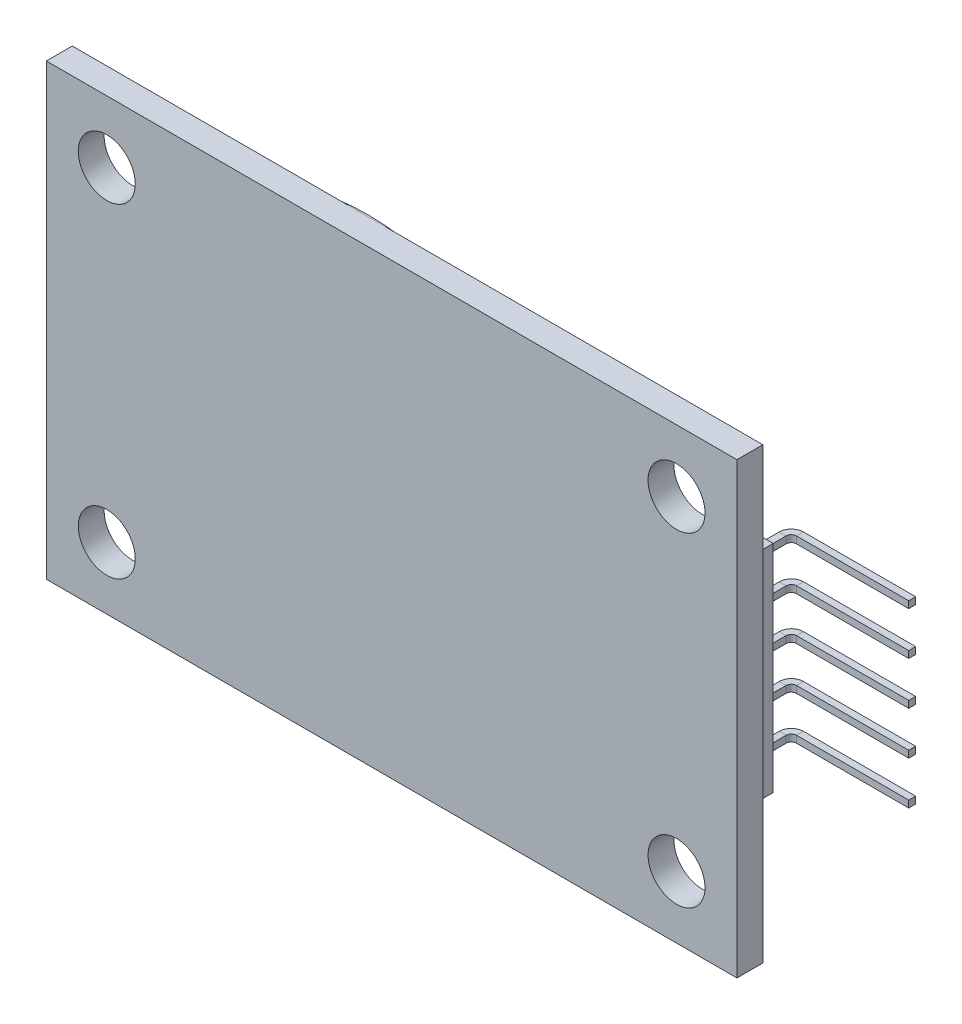
SolidWorks part; units mm, degrees
ref_plane "前视基准面" through (0, 0, 0) normal (0, 0, 1) x (1, 0, 0)
ref_plane "上视基准面" through (0, 0, 0) normal (0, 1, 0) x (1, 0, 0)
ref_plane "右视基准面" through (0, 0, 0) normal (1, 0, 0) x (0, 0, -1)
sketch "草图1" plane through (0, 0, 0) normal (0, 0, 1) x (1, 0, 0)
  line L1 (-20, 13) -> (20, 13)
  line L2 (-20, 13) -> (-20, -13)
  line L3 (-20, -13) -> (20, -13)
  line L4 (20, 13) -> (20, -13)
  line L5 (-20, 13) -> (20, -13) construction
  line L6 (-20, -13) -> (20, 13) construction
  point P0 (0, 0)
  dimension "D1" = 40
  dimension "D2" = 26
extrude "凸台-拉伸1" add sketch "草图1" along normal blind 1.5
sketch "草图2" plane through (0, 0, 1.5) normal (0, 0, 1) x (1, 0, 0)
  line L1 (-16.5, 9.4) -> (16.5, 9.4)
  line L2 (-16.5, 9.4) -> (-16.5, -9.4)
  line L3 (-16.5, -9.4) -> (16.5, -9.4)
  line L4 (16.5, 9.4) -> (16.5, -9.4)
  line L5 (-16.5, 9.4) -> (16.5, -9.4) construction
  line L6 (-16.5, -9.4) -> (16.5, 9.4) construction
  circle A0 centre (-16.5, 9.4) radius 1.65
  circle A1 centre (16.5, 9.4) radius 1.65
  circle A2 centre (16.5, -9.4) radius 1.65
  circle A3 centre (-16.5, -9.4) radius 1.65
  point P0 (0, 0)
  dimension "D3" = 3.3
  dimension "D4" = 3.3
  dimension "D5" = 3.3
  dimension "D6" = 3.3
  dimension "D1" = 33
  dimension "D2" = 18.8
extrude "切除-拉伸1" cut sketch "草图2" against normal blind 1.5 contours A0 | A1 | A3 | A2
sketch "草图3" plane through (0, 0, 0) normal (0, 0, -1) x (-1, 0, 0)
  line L0 (0, 0) -> (20, 0) construction
  line L1 (20, 13) -> (20, -13) construction
  circle A0 centre (3, 0) radius 13
  dimension "D1" = 17
extrude "凸台-拉伸2" add sketch "草图3" along normal blind 0.1 contours A0
sketch "草图4" plane through (0, 0, 0) normal (0, 0, -1) x (-1, 0, 0)
  line L0 (-20, 0) -> (20, 0) construction
  line L1 (-20, -13) -> (-20, 13) construction
  line L2 (20, 13) -> (20, -13) construction
  line L4 (-18.5, 6.25) -> (-16, 6.25)
  line L5 (-18.5, 6.25) -> (-18.5, -6.25)
  line L6 (-18.5, -6.25) -> (-16, -6.25)
  line L7 (-16, 6.25) -> (-16, -6.25)
  line L8 (-18.5, 6.25) -> (-16, -6.25) construction
  line L9 (-18.5, -6.25) -> (-16, 6.25) construction
  point P6 (-17.25, 0)
  dimension "D1" = 2.5
  dimension "D2" = 12.5
  dimension "D3" = 1.5
extrude "凸台-拉伸3" add sketch "草图4" along normal blind 2.1
sketch "草图5" plane through (0, 0, -2.1) normal (0, 0, -1) x (-1, 0, 0)
  line L0 (-18.5, 6.25) -> (-18.5, 3.75) construction
  line L1 (-18.5, 6.25) -> (-18.5, -6.25) construction
  line L2 (-18.5, 3.75) -> (-16, 3.75) construction
  line L3 (-16, -6.25) -> (-16, 6.25) construction
  line L4 (-18.5, 5) -> (-16, 5) construction
  line L5 (-16, 5) -> (-17.25, 3.75) construction
  line L6 (-17.25, 3.75) -> (-17.25, 5) construction
  line L7 (-17.45, 2.7) -> (-17.05, 2.7)
  line L8 (-17.45, 5.2) -> (-17.05, 5.2)
  line L9 (-17.45, 5.2) -> (-17.45, 4.8)
  line L10 (-17.45, 4.8) -> (-17.05, 4.8)
  line L11 (-17.05, 5.2) -> (-17.05, 4.8)
  line L12 (-17.45, 5.2) -> (-17.05, 4.8) construction
  line L13 (-17.45, 4.8) -> (-17.05, 5.2) construction
  line L14 (-17.45, 2.7) -> (-17.45, 2.3)
  line L15 (-17.45, 2.3) -> (-17.05, 2.3)
  line L16 (-17.05, 2.7) -> (-17.05, 2.3)
  line L17 (-17.45, 2.7) -> (-17.05, 2.3) construction
  line L18 (-17.45, 2.3) -> (-17.05, 2.7) construction
  line L19 (-17.45, 0.2) -> (-17.05, 0.2)
  line L20 (-17.45, 0.2) -> (-17.45, -0.2)
  line L21 (-17.45, -0.2) -> (-17.05, -0.2)
  line L22 (-17.05, 0.2) -> (-17.05, -0.2)
  line L23 (-17.45, 0.2) -> (-17.05, -0.2) construction
  line L24 (-17.45, -0.2) -> (-17.05, 0.2) construction
  line L25 (-17.45, -2.3) -> (-17.05, -2.3)
  line L26 (-17.45, -2.3) -> (-17.45, -2.7)
  line L27 (-17.45, -2.7) -> (-17.05, -2.7)
  line L28 (-17.05, -2.3) -> (-17.05, -2.7)
  line L29 (-17.45, -2.3) -> (-17.05, -2.7) construction
  line L30 (-17.45, -2.7) -> (-17.05, -2.3) construction
  line L31 (-17.45, -4.8) -> (-17.05, -4.8)
  line L32 (-17.45, -4.8) -> (-17.45, -5.2)
  line L33 (-17.45, -5.2) -> (-17.05, -5.2)
  line L34 (-17.05, -4.8) -> (-17.05, -5.2)
  line L35 (-17.45, -4.8) -> (-17.05, -5.2) construction
  line L36 (-17.45, -5.2) -> (-17.05, -4.8) construction
  dimension "D1" = 2.5
  dimension "D2" = 0.4
  dimension "D3" = 0.4
  dimension "D4" = 5
ref_plane "基准面1" through (0, 5.2, 0) normal (0, -1, 0) x (-1, 0, 0)
sketch "草图6" plane through (0, 5.2, 0) normal (0, -1, 0) x (-1, 0, 0)
  line L0 (-17.25, 2.1) -> (-17.25, 3.9)
  line L1 (-17.45, 2.1) -> (-17.05, 2.1) construction
  line L2 (-17.75, 4.4) -> (-24.25, 4.4)
  arc A0 (-17.25, 3.9) -> (-17.75, 4.4) centre (-17.75, 3.9) ccw
  point P7 (-17.25, 4.4)
  dimension "D3" = 0.5
  dimension "D1" = 2.3
  dimension "D2" = 7
sweep "扫描1" add profiles "草图5" path "草图6"
